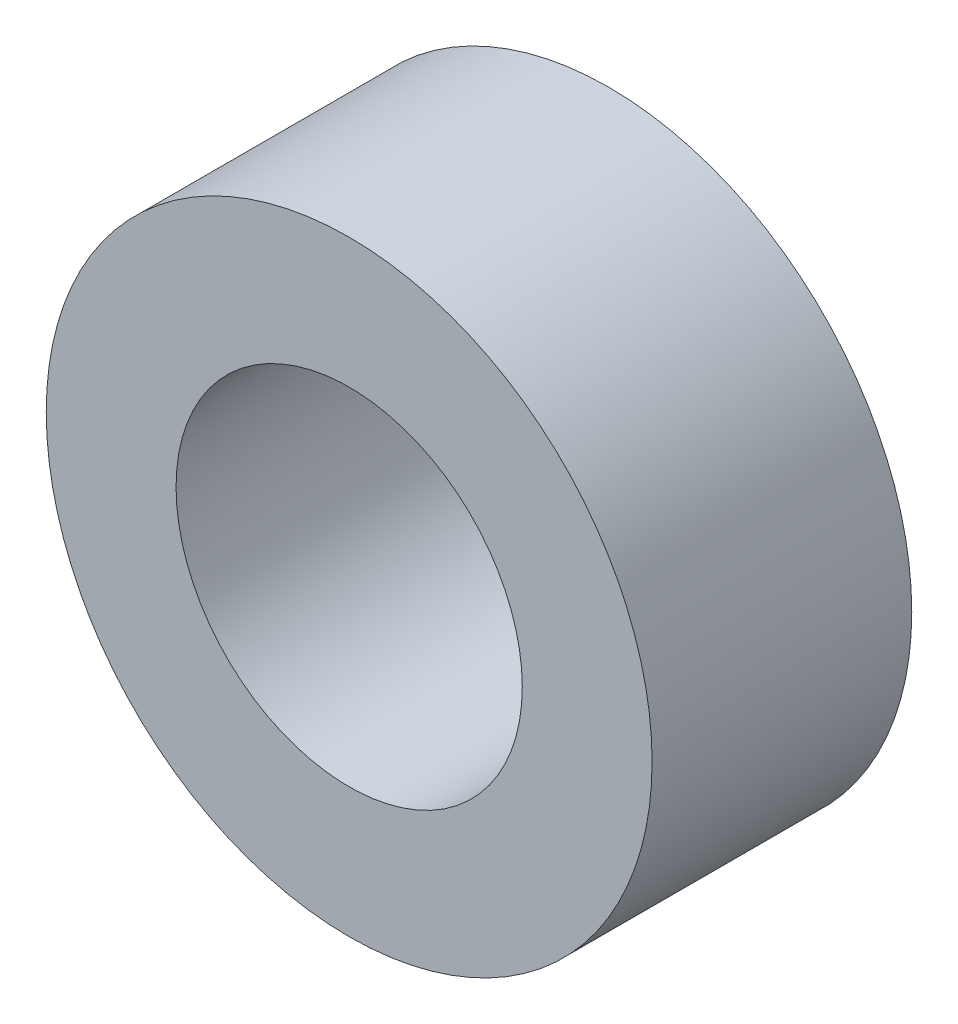
SolidWorks part; units mm, degrees
material "PEI"
ref_plane "Piano frontale" through (0, 0, 0) normal (0, 0, 1) x (1, 0, 0)
ref_plane "Piano superiore" through (0, 0, 0) normal (0, 1, 0) x (1, 0, 0)
ref_plane "Piano destro" through (0, 0, 0) normal (1, 0, 0) x (0, 0, -1)
sketch "Schizzo1" plane through (0, 0, 0) normal (0, 0, 1) x (1, 0, 0)
  circle A0 centre (0, 0) radius 4
  circle A1 centre (0, 0) radius 7
  dimension "D1" = 8
  dimension "D2" = 14
extrude "Estrusione-Estrusione1" add sketch "Schizzo1" along normal blind 6
